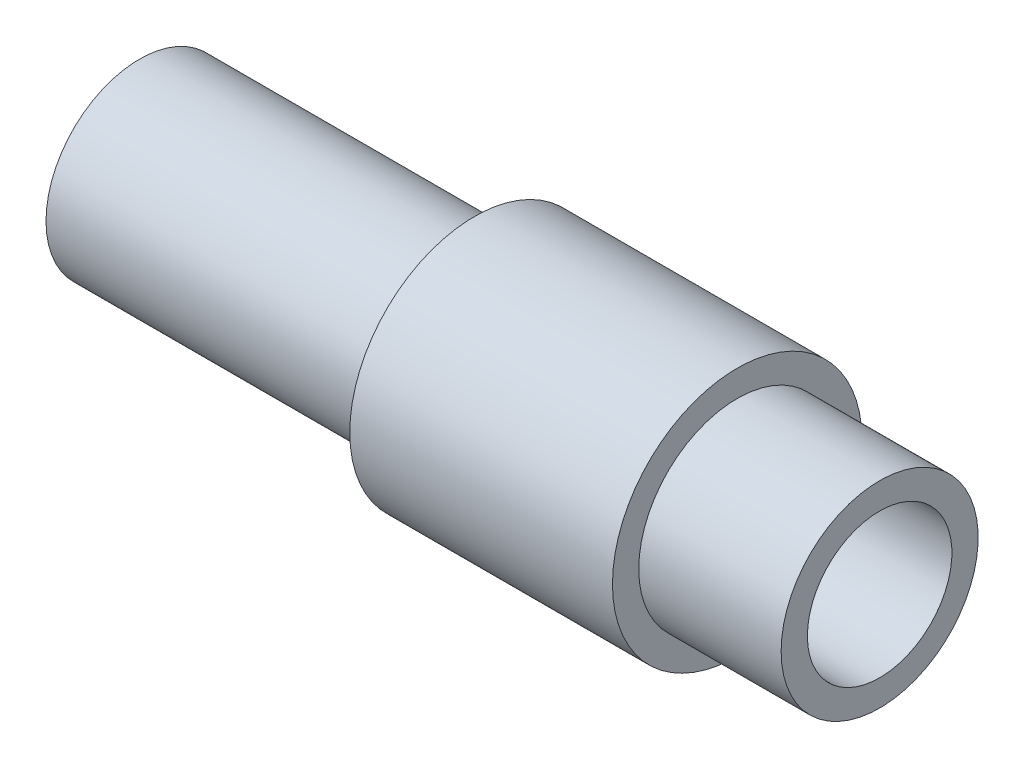
SolidWorks part; units mm, degrees
ref_plane "Front Plane" through (0, 0, 0) normal (0, 0, 1) x (1, 0, 0)
ref_plane "Top Plane" through (0, 0, 0) normal (0, 1, 0) x (1, 0, 0)
ref_plane "Right Plane" through (0, 0, 0) normal (1, 0, 0) x (0, 0, -1)
sketch "Sketch1" plane through (0, 0, 0) normal (0, 0, 1) x (1, 0, 0)
  line L0 (-83.6737, 19.6329) -> (88.7001, 19.6329) construction
  line L1 (-72.1427, 24.7579) -> (-44.6427, 24.7579)
  line L2 (-72.1427, 26.7579) -> (-46.6427, 26.7579)
  line L3 (-46.6427, 26.7579) -> (-46.6427, 29.1329)
  line L4 (-46.6427, 29.1329) -> (-26.6427, 29.1329)
  line L5 (-44.6427, 24.7579) -> (-44.6427, 27.1329)
  line L7 (-72.1427, 26.7579) -> (-72.1427, 24.7579)
  line L9 (-44.6427, 27.1329) -> (-26.6427, 27.1329) construction
  line L10 (-26.6427, 29.1329) -> (-26.6427, 27.1329)
  line L11 (-26.6427, 27.1329) -> (-15.8035, 27.1329)
  line L18 (-28.6427, 27.1329) -> (-28.6427, 25.1329)
  line L19 (-28.6427, 25.1329) -> (-15.8035, 25.1329)
  line L21 (-15.8035, 27.1329) -> (-15.8035, 25.1329)
  line L22 (-42.6427, 27.1329) -> (-28.6427, 27.1329) construction
  line L23 (-42.6427, 27.1329) -> (-42.6427, 27.1329) construction
  line L24 (-42.6427, 27.1329) -> (-42.6427, 27.1329) construction
  line L25 (-42.6427, 27.1329) -> (-42.6427, 27.1329) construction
  line L26 (-42.6427, 27.1329) -> (-42.6427, 27.1329) construction
  line L27 (-42.6427, 27.1329) -> (-42.6427, 27.1329) construction
  line L28 (-44.6427, 27.1329) -> (-28.6427, 27.1329)
  dimension "D2" = 14.25
  dimension "D3" = 25.5
  dimension "D4" = 20
  dimension "D5" = 19
  dimension "D7" = 15
  dimension "D1" = 2
  dimension "D6" = 2
revolve "Revolve1" add sketch "Sketch1" angle 360 about L0
